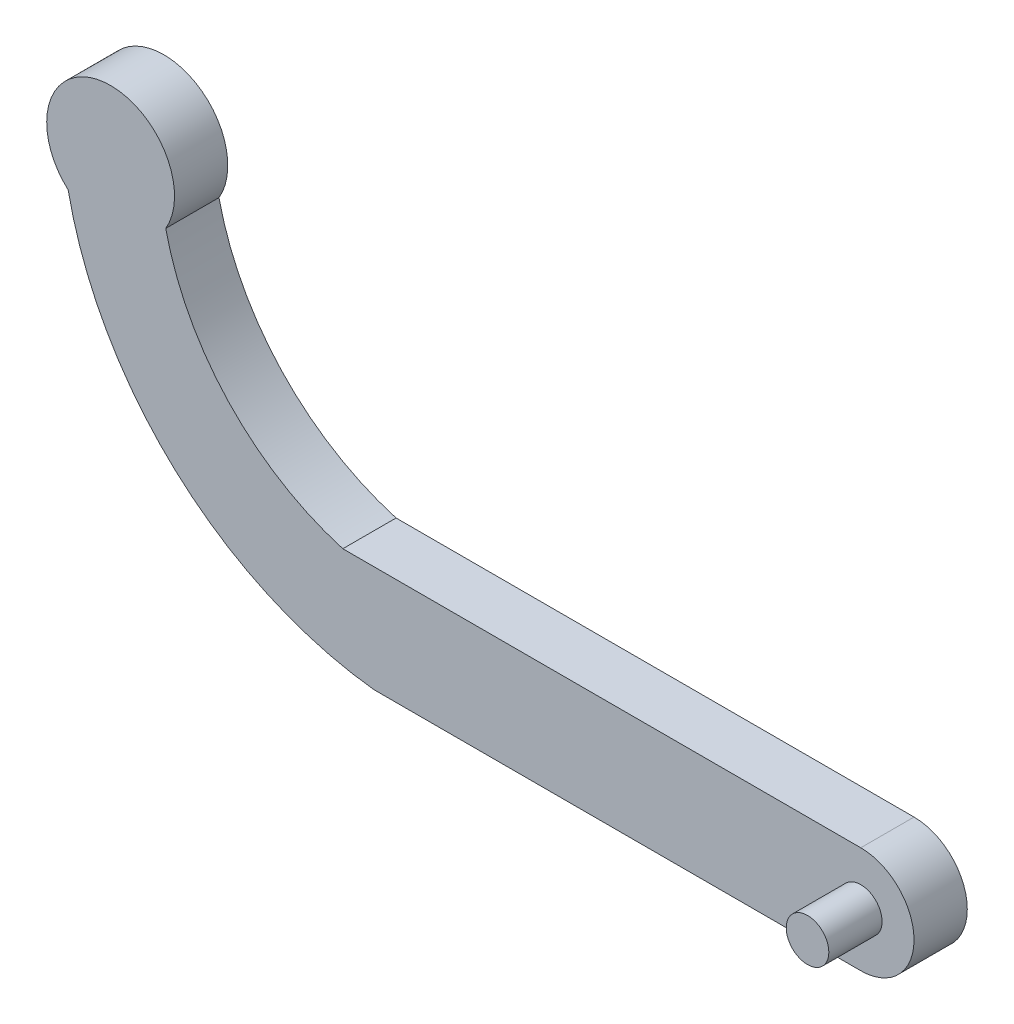
SolidWorks part; units mm, degrees
ref_plane "Alzado" through (0, 0, 0) normal (0, 0, 1) x (1, 0, 0)
ref_plane "Planta" through (0, 0, 0) normal (0, 1, 0) x (1, 0, 0)
ref_plane "Vista lateral" through (0, 0, 0) normal (1, 0, 0) x (0, 0, -1)
sketch "Croquis1" plane through (0, 0, 0) normal (0, 0, 1) x (1, 0, 0)
  line L1 (-25.9537, 5.8047) -> (22.6781, 5.8047)
  line L3 (-23.0472, -4.1953) -> (22.6781, -4.1953)
  arc A1 (22.6781, -4.1953) -> (22.6781, 5.8047) centre (22.6781, 0.8047) ccw
  arc A5 (-42.5787, 23.5412) -> (-25.9537, 5.8047) centre (-19.2925, 28.7084) ccw
  arc A8 (-42.5787, 23.5412) -> (-51.7413, 22.0883) centre (-47.7561, 26.5736) ccw
  arc A9 (-51.7413, 22.0883) -> (-23.0472, -4.1953) centre (-19.2925, 28.7084) ccw
  dimension "D2" = 6
  dimension "D3" = 5
  dimension "D7" = 23.8527
  dimension "D8" = 33.1172
  dimension "D5" = 10
  dimension "D9" = 75
extrude "Saliente-Extruir1" add sketch "Croquis1" along normal blind 5
sketch "Croquis2" plane through (0, 0, 5) normal (0, 0, 1) x (1, 0, 0)
  circle A0 centre (22.6781, 0.8047) radius 2
  dimension "D1" = 4
extrude "Saliente-Extruir2" add sketch "Croquis2" along normal blind 5
